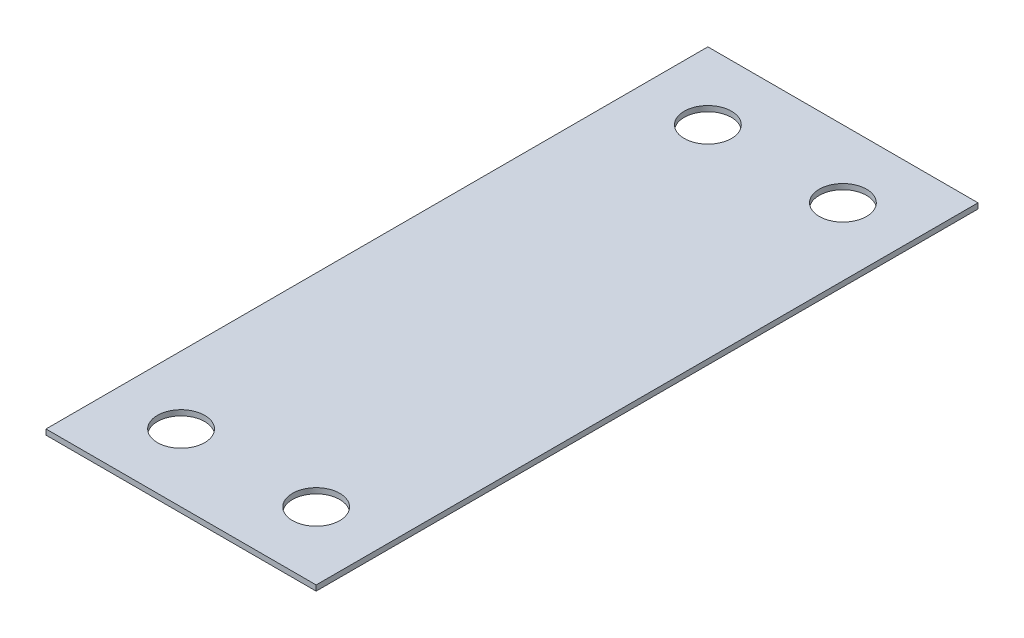
SolidWorks part; units mm, degrees
ref_plane "Front Plane" through (0, 0, 0) normal (0, 0, 1) x (1, 0, 0)
ref_plane "Top Plane" through (0, 0, 0) normal (0, 1, 0) x (1, 0, 0)
ref_plane "Right Plane" through (0, 0, 0) normal (1, 0, 0) x (0, 0, -1)
sketch "Sketch1" plane through (0, 0, 0) normal (0, 1, 0) x (1, 0, 0)
  line L0 (0, 0) -> (20, 0)
  line L1 (20, 0) -> (20, 10)
  line L2 (20, 10) -> (20, 35)
  line L3 (20, 35) -> (20, 49)
  line L4 (20, 49) -> (0, 49)
  line L5 (0, 49) -> (0, 0)
  line L6 (10, 49) -> (10, 0) construction
  line L7 (20, 22.5) -> (0, 22.5) construction
  circle A0 centre (5, 44) radius 1.75
  circle A1 centre (15, 44) radius 1.75
  circle A2 centre (15, 5) radius 1.75
  circle A3 centre (5, 5) radius 1.75
  dimension "D5" = 3.5
  dimension "D1" = 20
  dimension "D2" = 10
  dimension "D3" = 14
  dimension "D4" = 25
  dimension "D6" = 5
  dimension "D7" = 5
  dimension "D8" = 5
extrude "Boss-Extrude1" add sketch "Sketch1" along normal blind 0.4
equation "\"length\"= 25"
equation "\"D4@Sketch1\"=\"length\""
equation "\"top_length\"= 14"
equation "\"D3@Sketch1\"=\"top_length\""
